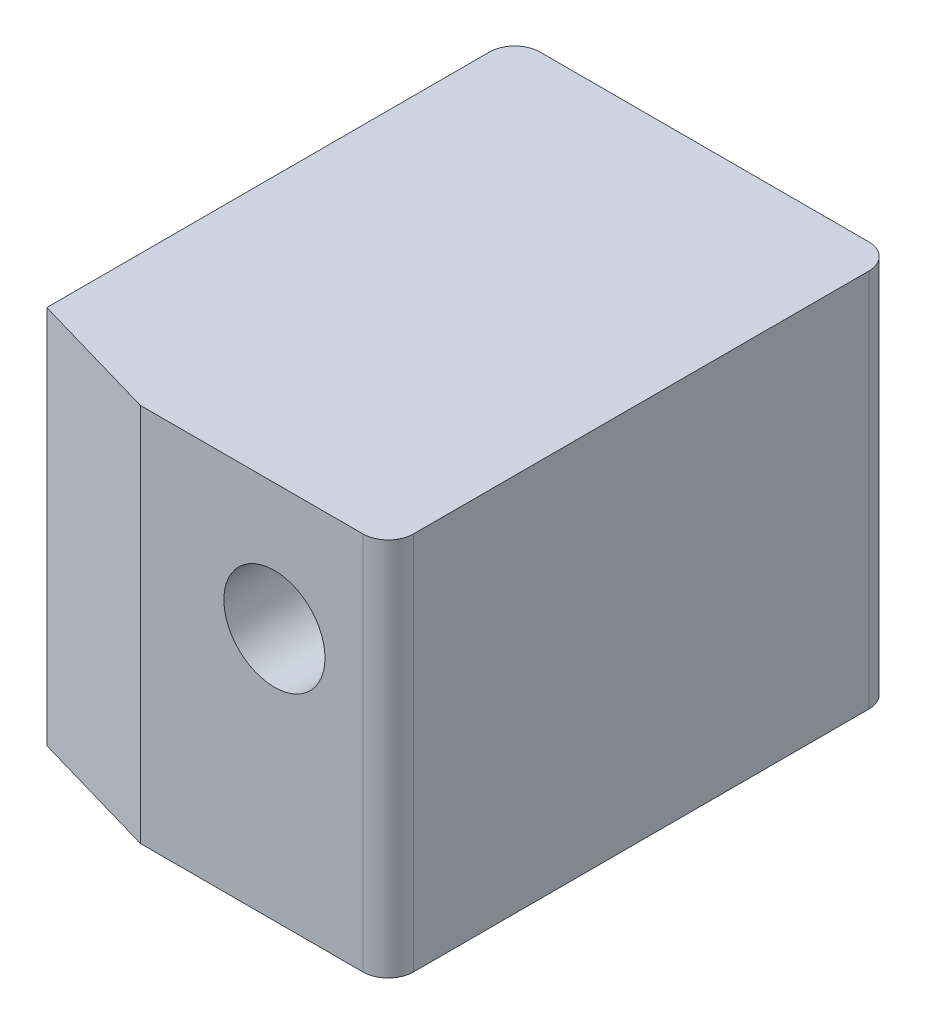
SolidWorks part; units mm, degrees
ref_plane "Plan de face" through (0, 0, 0) normal (0, 0, 1) x (1, 0, 0)
ref_plane "Plan de dessus" through (0, 0, 0) normal (0, 1, 0) x (1, 0, 0)
ref_plane "Plan de droite" through (0, 0, 0) normal (1, 0, 0) x (0, 0, -1)
sketch "Esquisse1" plane through (0, 0, 0) normal (0, 1, 0) x (1, 0, 0)
  line L0 (0, 0) -> (7.5, 0)
  line L1 (0, 0) -> (-7.5, 0)
  line L2 (-7.5, 0) -> (-7.5, 20)
  line L3 (-7.5, 20) -> (7.5, 20)
  line L4 (7.5, 20) -> (7.5, 0)
  dimension "D1" = 20
  dimension "D2" = 15
extrude "Boss.-Extru.1" add sketch "Esquisse1" along normal blind 15
sketch "Esquisse2" plane through (0, 0, 0) normal (0, -1, 0) x (1, 0, 0)
  line L0 (-7.5, -20) -> (-7.5, -16) construction
  line L1 (-7.5, -20) -> (-7.5, 0) construction
  line L2 (-7.5, 0) -> (-7.5, -4) construction
  line L3 (7.5, 0) -> (7.5, -20) construction
  line L4 (-7.5, -4) -> (1.5, -4) construction
  line L5 (-1.5, -16) -> (7.5, -16) construction
  circle A4 centre (3, -16) radius 2
  circle A5 centre (-3, -4) radius 2
  dimension "D2" = 9
  dimension "D3" = 4
  dimension "D1" = 4
  dimension "D4" = 9
extrude "Enlèv. mat.-Extru.1" cut sketch "Esquisse2" against normal blind 12
sketch "Esquisse3" plane through (0, 0, 0) normal (0, 0, 1) x (1, 0, 0)
  line L0 (-7.5, 0) -> (3, 0) construction
  line L1 (-7.5, 0) -> (7.5, 0) construction
  line L2 (3, 0) -> (3, 10) construction
  circle A1 centre (3, 10) radius 2
  dimension "D1" = 10.5
  dimension "D3" = 4
  dimension "D2" = 10
extrude "Enlèv. mat.-Extru.2" cut sketch "Esquisse3" against normal blind 12
fillet "Congé1" radius 1 3 edges at (7.5, 7.5, -20) (-7.5, 7.5, -20) (7.5, 7.5, 0)
sketch "Esquisse4" plane through (0, 15, 0) normal (0, 1, 0) x (1, 0, 0)
  line L0 (-7.5, 0) -> (-2.3, 0)
  line L1 (-7.5, 0) -> (6.5, 0) construction
  line L2 (-7.5, 0) -> (-7.5, 1.5)
  line L3 (-7.5, 19) -> (-7.5, 0) construction
  line L4 (-7.5, 1.5) -> (-2.3, 0)
  dimension "D1" = 1.5
  dimension "D2" = 5.2
extrude "Enlèv. mat.-Extru.3" cut sketch "Esquisse4" against normal up to next
